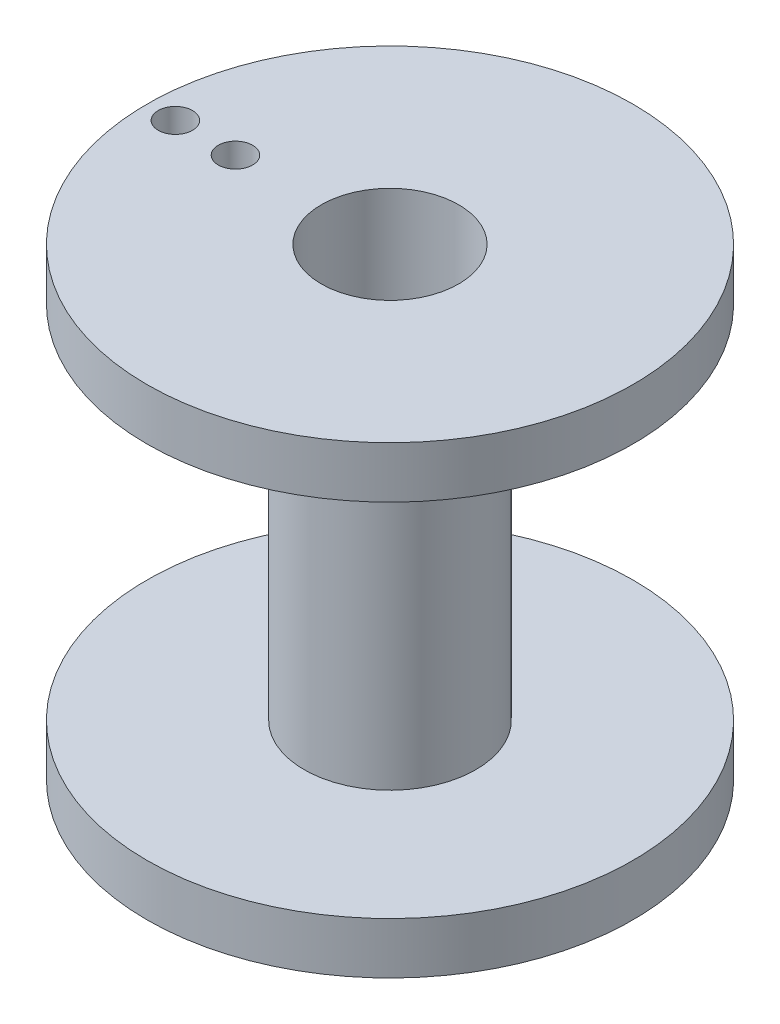
SolidWorks part; units mm, degrees
other "Markup1"
sketch "Sketch6" plane through (14.15, 0, -14.15) normal (0.2934, -0.0939, -0.9514) x (-0.4009, -0.9155, -0.0333)
ref_plane "Front Plane" through (0, 0, 0) normal (0, 0, 1) x (1, 0, 0)
ref_plane "Top Plane" through (0, 0, 0) normal (0, 1, 0) x (1, 0, 0)
ref_plane "Right Plane" through (0, 0, 0) normal (1, 0, 0) x (0, 0, -1)
sketch "Sketch1" plane through (0, 0, 0) normal (0, 1, 0) x (1, 0, 0)
  circle A0 centre (0, 0) radius 14.15
  dimension "D1" = 28.3
extrude "Boss-Extrude1" add sketch "Sketch1" along normal blind 3
sketch "Sketch2" plane through (0, 3, 0) normal (0, 1, 0) x (1, 0, 0)
  circle A0 centre (0, 0) radius 5
  dimension "D1" = 10
extrude "Boss-Extrude2" add sketch "Sketch2" along normal blind 21
sketch "Sketch3" plane through (0, 24, 0) normal (0, 1, 0) x (1, 0, 0)
  circle A0 centre (0, 0) radius 14.15
  dimension "D1" = 28.3
extrude "Boss-Extrude3" add sketch "Sketch3" along normal blind 3
sketch "Sketch4" plane through (0, 27, 0) normal (0, 1, 0) x (1, 0, 0)
  circle A0 centre (0, 0) radius 4
  dimension "D1" = 8
extrude "Cut-Extrude1" cut sketch "Sketch4" against normal through all
sketch "Sketch5" plane through (0, 27, 0) normal (0, 1, 0) x (1, 0, 0)
  circle A0 centre (-9, 0) radius 1
  circle A1 centre (-12.5, 0) radius 1
  dimension "D1" = 2
  dimension "D2" = 2
  dimension "D3" = 9
  dimension "D4" = 12.5
extrude "Cut-Extrude2" cut sketch "Sketch5" against normal up to next
